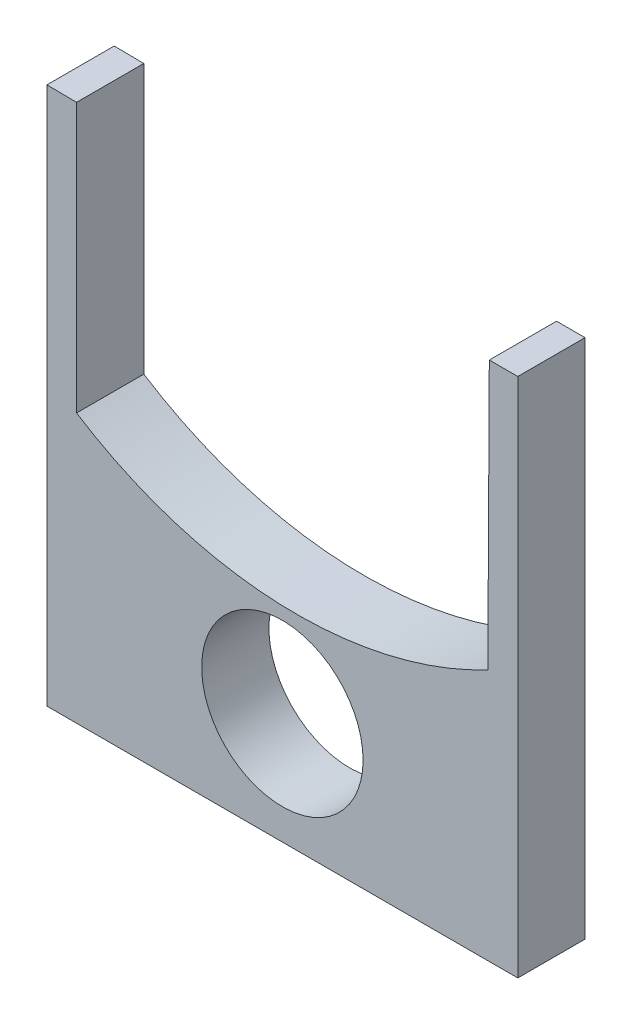
SolidWorks part; units mm, degrees
ref_plane "Front Plane" through (0, 0, 0) normal (0, 0, 1) x (1, 0, 0)
ref_plane "Top Plane" through (0, 0, 0) normal (0, 1, 0) x (1, 0, 0)
ref_plane "Right Plane" through (0, 0, 0) normal (1, 0, 0) x (0, 0, -1)
sketch "Sketch1" plane through (0, 0, 0) normal (0, 0, 1) x (1, 0, 0)
  line L0 (-17.5, 13.936) -> (-15.3001, 13.9108)
  line L1 (17.5, -26.064) -> (-17.5, -26.064)
  line L2 (17.5, -26.064) -> (17.5, 12.6612)
  line L4 (-17.5, -26.064) -> (-17.5, 13.936)
  line L5 (17.5, 12.6612) -> (15.3824, 12.6612)
  line L6 (-15.3001, 13.9108) -> (-15.3001, -6.0892)
  line L7 (15.3824, 12.6612) -> (15.2725, -7.3385)
  circle A1 centre (0, -17.7865) radius 6
  arc A2 (15.2725, -7.3385) -> (-15.3001, -6.0892) centre (1.0586, 19.5319) cw
  point P0 (0, -17.7865)
  point P8 (0, 0)
  point P10 (0, -26.064)
  point P11 (0, -12.9469)
  point P12 (0, -17.7865)
extrude "Boss-Extrude1" add sketch "Sketch1" along normal blind 5
